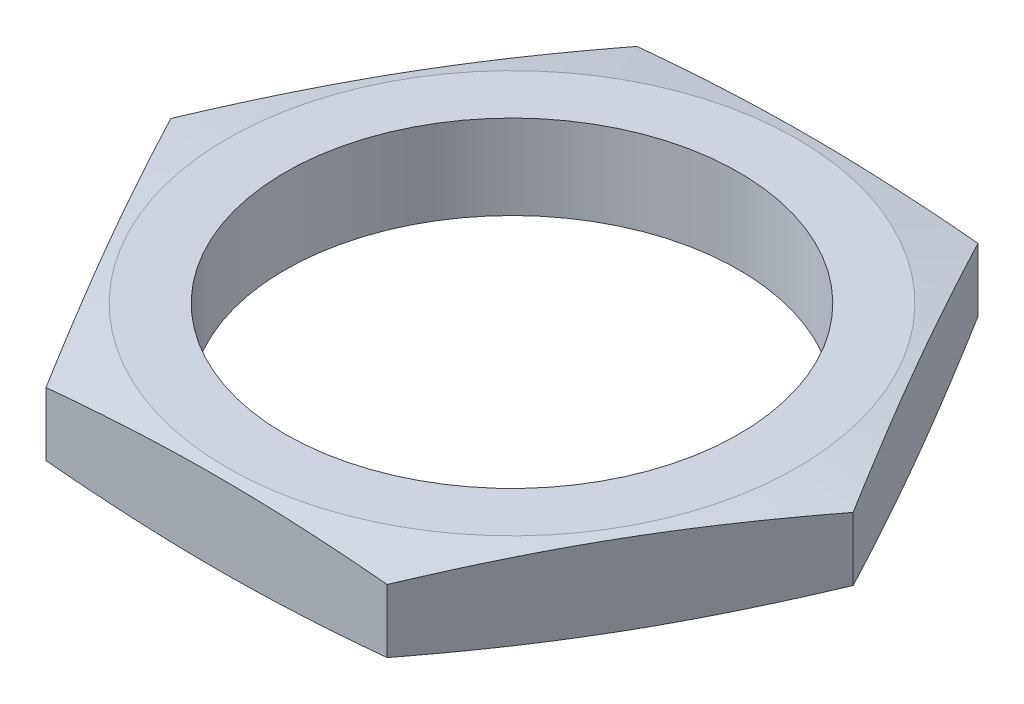
SolidWorks part; units mm, degrees
ref_plane "前视基准面" through (0, 0, 0) normal (0, 0, 1) x (1, 0, 0)
ref_plane "上视基准面" through (0, 0, 0) normal (0, 1, 0) x (1, 0, 0)
ref_plane "右视基准面" through (0, 0, 0) normal (1, 0, 0) x (0, 0, -1)
sketch "草图1" plane through (0, 0, 0) normal (0, 1, 0) x (1, 0, 0)
  line L0 (0, 0) -> (25.6788, 0) construction
  line L1 (8.0829, 14) -> (-8.0829, 14)
  line L2 (-8.0829, 14) -> (-16.1658, 0)
  line L3 (-16.1658, 0) -> (-8.0829, -14)
  line L4 (-8.0829, -14) -> (8.0829, -14)
  line L5 (8.0829, -14) -> (16.1658, 0)
  line L6 (16.1658, 0) -> (8.0829, 14)
  circle A0 centre (0, 0) radius 14 construction
  point P10 (0, 0)
  dimension "D1" = 28
extrude "凸台-拉伸1" add sketch "草图1" along normal blind 4
sketch "草图2" plane through (0, 4, 0) normal (0, 1, 0) x (1, 0, 0)
  circle A0 centre (0, 0) radius 10.75
  dimension "D1" = 21.5
extrude "切除-拉伸1" cut sketch "草图2" against normal through all
sketch "草图3" plane through (0, 0, 0) normal (0, 0, 1) x (1, 0, 0)
  line L0 (-16.1658, 4) -> (-16.1658, 3.5)
  line L1 (-16.1658, 4) -> (-16.1658, 0) construction
  line L2 (-16.1658, 3.5) -> (-13.5, 4)
  line L3 (-16.1658, 4) -> (-8.0829, 4) construction
  line L4 (-13.5, 4) -> (-16.1658, 4)
  line L5 (0, 0) -> (0, 11.339) construction
  line L6 (-20.2504, 2) -> (-12.0812, 2) construction
  line L7 (-13.5, 0) -> (-16.1658, 0)
  line L8 (-16.1658, 0.5) -> (-13.5, 0)
  line L9 (-16.1658, 0) -> (-16.1658, 0.5)
  point P14 (-16.1658, 2)
  dimension "D1" = 13.5
  dimension "D2" = 0.5
revolve "切除-旋转1" cut sketch "草图3" angle 360 about L5
